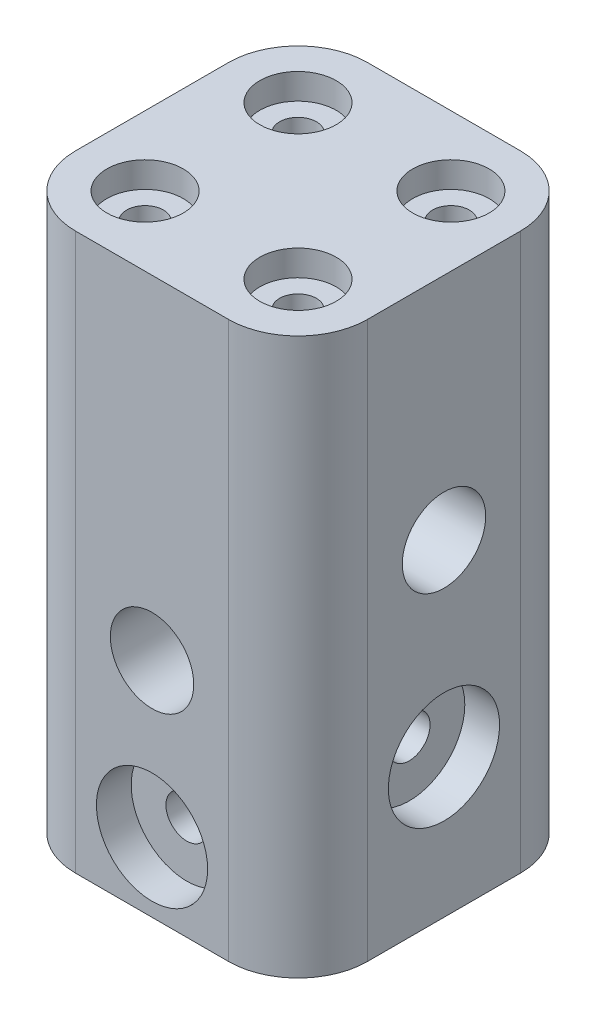
SolidWorks part; units mm, degrees
ref_plane "Front Plane" through (0, 0, 0) normal (0, 0, 1) x (1, 0, 0)
ref_plane "Top Plane" through (0, 0, 0) normal (0, 1, 0) x (1, 0, 0)
ref_plane "Right Plane" through (0, 0, 0) normal (1, 0, 0) x (0, 0, -1)
sketch "Sketch1" plane through (0, 0, 0) normal (0, 1, 0) x (1, 0, 0)
  line L1 (-21, 21) -> (21, 21)
  line L2 (-21, 21) -> (-21, -21)
  line L3 (-21, -21) -> (21, -21)
  line L4 (21, 21) -> (21, -21)
  line L5 (-21, 21) -> (21, -21) construction
  line L6 (-21, -21) -> (21, 21) construction
  point P0 (0, 0)
  dimension "D1" = 42
  dimension "D2" = 42
extrude "Boss-Extrude1" add sketch "Sketch1" along normal blind 80
sketch "Sketch2" plane through (0, 0, 21) normal (0, 0, 1) x (1, 0, 0)
  line L0 (-21, 0) -> (21, 0) construction
  line L1 (0, -1000) -> (0, 49000) construction
  circle A0 centre (0, 32) radius 6
  point P7 (0, 0)
  dimension "D1" = 12
  dimension "D2" = 32
extrude "Cut-Extrude1" cut sketch "Sketch2" against normal through all
sketch "Sketch3" plane through (21, 0, 0) normal (1, 0, 0) x (0, 0, -1)
  line L0 (0, -1000) -> (0, 49000) construction
  circle A0 centre (0, 47) radius 6
  dimension "D1" = 12
  dimension "D2" = 47
extrude "Cut-Extrude2" cut sketch "Sketch3" against normal through all
sketch "Sketch4" plane through (0, 0, 21) normal (0, 0, 1) x (1, 0, 0)
  line L1 (-21, 0) -> (21, 0) construction
  line L2 (0, 0) -> (0, 80) construction
  line L3 (-21, 80) -> (21, 80) construction
  circle A0 centre (0, 10) radius 3
  dimension "D1" = 6
  dimension "D2" = 10
extrude "Cut-Extrude3" cut sketch "Sketch4" against normal through all
sketch "Sketch5" plane through (0, 0, 21) normal (0, 0, 1) x (1, 0, 0)
  circle A0 centre (0, 10) radius 8
  dimension "D1" = 16
extrude "Cut-Extrude4" cut sketch "Sketch5" against normal blind 5
sketch "Sketch6" plane through (0, 0, -21) normal (0, 0, -1) x (-1, 0, 0)
  circle A0 centre (0, 10) radius 8
  dimension "D1" = 16
extrude "Cut-Extrude5" cut sketch "Sketch6" against normal blind 5
sketch "Sketch7" plane through (21, 0, 0) normal (1, 0, 0) x (0, 0, -1)
  line L0 (0, -1000) -> (0, 49000) construction
  line L1 (-21, 0) -> (21, 0) construction
  circle A0 centre (0, 20) radius 3
  dimension "D1" = 6
  dimension "D2" = 20
extrude "Cut-Extrude6" cut sketch "Sketch7" against normal through all
sketch "Sketch8" plane through (21, 0, 0) normal (1, 0, 0) x (0, 0, -1)
  circle A0 centre (0, 20) radius 8
  dimension "D1" = 16
extrude "Cut-Extrude7" cut sketch "Sketch8" against normal blind 5
sketch "Sketch9" plane through (-21, 0, 0) normal (-1, 0, 0) x (0, 0, 1)
  circle A0 centre (0, 20) radius 8
  dimension "D1" = 16
extrude "Cut-Extrude8" cut sketch "Sketch9" against normal blind 5
fillet "Fillet1" radius 10 4 edges at (21, 40, 21) (21, 40, -21) (-21, 40, 21) (-21, 40, -21)
hole_wizard "CBORE for M5 Pan Head Machine Screw1" positions "Sketch11" profile "Sketch10" counterbore size "M5" standard "ANSI Metric" end condition through all
sketch "Sketch11" plane through (0, 80, 0) normal (0, 1, 0) x (1, 0, 0)
  line L0 (-21, 11) -> (-21, -11) construction
  line L1 (11, 21) -> (-11, 21) construction
  line L2 (21, -11) -> (21, 11) construction
  line L3 (-11, -21) -> (11, -21) construction
  point P0 (-11, 11)
  point P2 (11, 11)
  point P4 (11, -11)
  point P6 (-11, -11)
  dimension "D1" = 10
  dimension "D2" = 10
  dimension "D3" = 10
  dimension "D4" = 10
  dimension "D5" = 10
  dimension "D6" = 10
  dimension "D7" = 10
  dimension "D8" = 10
sketch "Sketch10" plane through (-11, 80, -11) normal (1, 0, 0) x (0, 0, 1)
  line L0 (0, 0) -> (0, 80)
  line L1 (0, 80) -> (2.65, 80)
  line L3 (2.65, 80) -> (2.65, 3.7)
  line L4 (2.65, 3.7) -> (5.5, 3.7)
  line L5 (5.5, 3.7) -> (5.5, 0)
  line L7 (5.5, 0) -> (0, 0)
  line L11 (0, -6.35) -> (0, 107.95) construction
  dimension "Thru Hole Dia." = 5.3
  dimension "Thru Hole Depth" = 80
  dimension "C'Bore Dia." = 11
  dimension "C'Bore Depth" = 3.7
